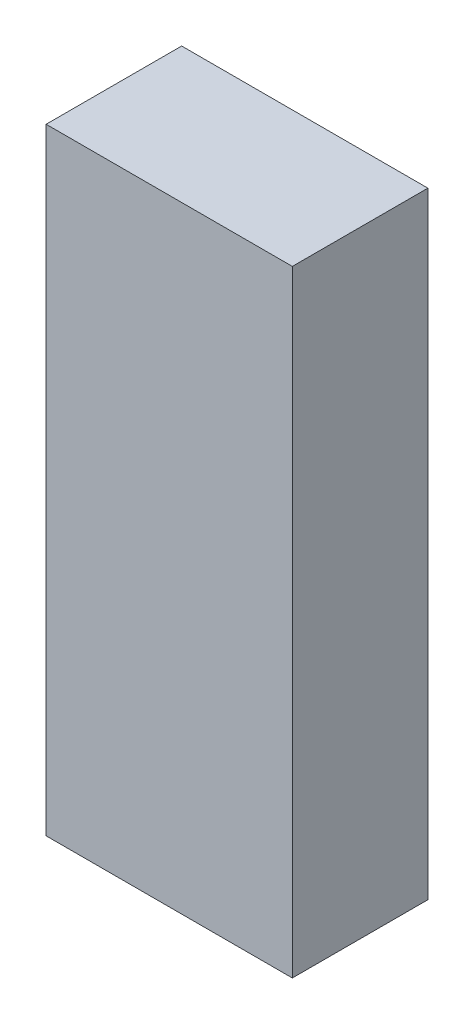
SolidWorks part; units mm, degrees
ref_plane "Front Plane" through (0, 0, 0) normal (0, 0, 1) x (1, 0, 0)
ref_plane "Top Plane" through (0, 0, 0) normal (0, 1, 0) x (1, 0, 0)
ref_plane "Right Plane" through (0, 0, 0) normal (1, 0, 0) x (0, 0, -1)
sketch "Sketch1" plane through (0, 0, 0) normal (0, 0, 1) x (1, 0, 0)
  line L1 (0, 0) -> (27.686, 0)
  line L2 (0, 0) -> (0, 69.3)
  line L3 (0, 69.3) -> (27.686, 69.3)
  line L4 (27.686, 0) -> (27.686, 69.3)
  dimension "D1" = 27.686
  dimension "D2" = 69.3
extrude "Boss-Extrude1" add sketch "Sketch1" along normal blind 15.24
equation "\"MDF\"= .3"
equation "\"Foamcore\"= .1"
equation "\"GMaterial\"= .6"
equation "\"CutDistance\" = .1"
equation "\"D1@Boss-Extrude1\"=\"GMaterial\""
